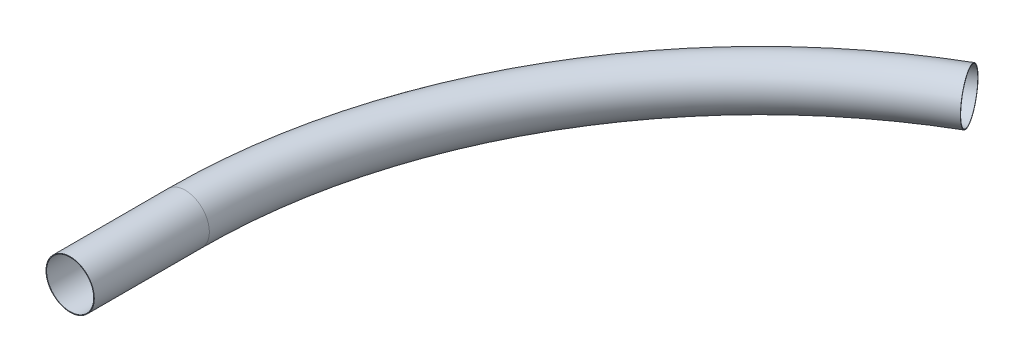
SolidWorks part; units mm, degrees
ref_plane "前视基准面" through (0, 0, 0) normal (0, 0, 1) x (1, 0, 0)
ref_plane "上视基准面" through (0, 0, 0) normal (0, 1, 0) x (1, 0, 0)
ref_plane "右视基准面" through (0, 0, 0) normal (1, 0, 0) x (0, 0, -1)
sketch "草图1" plane through (0, 0, 0) normal (0, 0, 1) x (1, 0, 0)
  line L0 (231, 0) -> (-231, 0) construction
  circle A0 centre (0, 0) radius 205
  circle A1 centre (0, 0) radius 210
  dimension "D1" = 410
  dimension "D2" = 420
sketch "草图2" plane through (0, 0, 0) normal (0, 1, 0) x (1, 0, 0)
  line L0 (0, 0) -> (0, 1000)
  arc A0 (0, 1000) -> (2491.5234, 5325.2219) centre (5000, 1000) cw
  dimension "D2" = 5000
  dimension "D1" = 1000
sweep "扫描1" add profiles "草图1" path "草图2"
